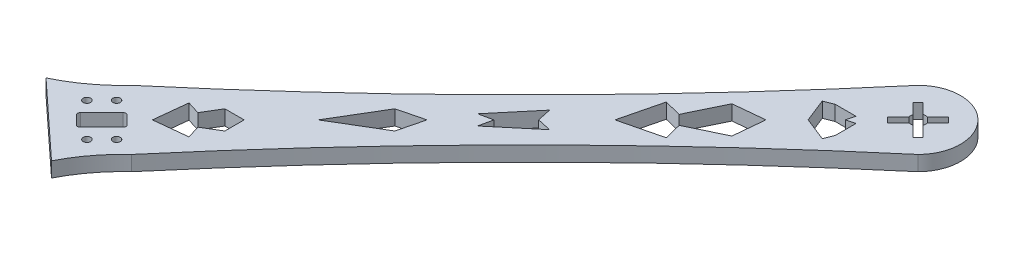
SolidWorks part; units mm, degrees
ref_plane "Front Plane" through (0, 0, 0) normal (0, 0, 1) x (1, 0, 0)
ref_plane "Top Plane" through (0, 0, 0) normal (0, 1, 0) x (1, 0, 0)
ref_plane "Right Plane" through (0, 0, 0) normal (1, 0, 0) x (0, 0, -1)
sketch "Sketch1" plane through (0, 0, 0) normal (0, 1, 0) x (1, 0, 0)
  line L4 (187.3513, 164.2611) -> (185.6543, 165.9582)
  line L5 (185.6543, 165.9582) -> (182.1188, 162.4226)
  line L6 (187.3513, 164.2611) -> (183.8158, 160.7256)
  line L7 (47.8787, 29.3076) -> (50.7071, 26.4792)
  line L8 (50.7071, 25.065) -> (43.636, 17.9939)
  line L9 (42.2218, 17.9939) -> (39.3934, 20.8224)
  line L10 (46.4645, 29.3076) -> (39.3934, 22.2366)
  line L11 (23.6, 26.4792) -> (48.4893, 3.4306)
  line L13 (187.3513, 155.7855) -> (183.8158, 159.321)
  line L14 (185.6543, 154.0884) -> (182.1188, 157.624)
  line L15 (185.6543, 154.0884) -> (187.3513, 155.7855)
  line L16 (177.1787, 154.0884) -> (180.7142, 157.624)
  line L17 (175.4816, 155.7855) -> (179.0171, 159.321)
  line L18 (175.4816, 155.7855) -> (177.1787, 154.0884)
  line L19 (175.4816, 164.2611) -> (179.0171, 160.7256)
  line L20 (177.1787, 165.9582) -> (180.7142, 162.4226)
  line L21 (177.1787, 165.9582) -> (175.4816, 164.2611)
  line L22 (186.5028, 165.1096) -> (191.4182, 170.025)
  arc A4 (43.636, 17.9939) -> (42.2218, 17.9939) centre (42.9289, 18.701) cw
  arc A5 (50.7071, 26.4792) -> (50.7071, 25.065) centre (50, 25.7721) cw
  arc A6 (39.3934, 22.2366) -> (39.3934, 20.8224) centre (40.1005, 21.5295) ccw
  arc A7 (47.8787, 29.3076) -> (46.4645, 29.3076) centre (47.1716, 28.6005) ccw
  circle A8 centre (41.8683, 31.7825) radius 1.25
  circle A9 centre (36.9185, 26.8328) radius 1.25
  circle A10 centre (48.2322, 15.5191) radius 1.25
  circle A11 centre (53.182, 20.4688) radius 1.25
  arc A12 (23.6, 26.4792) -> (40, 38.6005) centre (0, 75.5648) ccw
  arc A13 (48.4893, 3.4306) -> (59.9937, 18.6068) centre (96.9761, -21.3765) cw
  arc A14 (171.4214, 170.0219) -> (191.4151, 150.0282) centre (181.4165, 160.0233) cw
  arc A15 (40, 38.6005) -> (171.4214, 170.0219) centre (-675.445, 885.4669) ccw
  arc A16 (59.9937, 18.6068) -> (191.4151, 150.0282) centre (906.86, -696.8381) cw
  arc A17 (179.0171, 160.7256) -> (179.0171, 159.321) centre (181.4165, 160.0233) ccw
  arc A18 (182.1188, 162.4226) -> (180.7142, 162.4226) centre (181.4165, 160.0233) ccw
  arc A19 (180.7142, 157.624) -> (182.1188, 157.624) centre (181.4165, 160.0233) ccw
  arc A20 (183.8158, 159.321) -> (183.8158, 160.7256) centre (181.4165, 160.0233) ccw
  point P16 (186.5028, 165.1096)
  point P30 (42.9289, 17.2868)
  point P33 (51.4142, 25.7721)
  point P37 (40.8076, 19.4081)
  point P40 (49.2929, 27.8934)
  point P58 (181.4165, 160.0233)
  dimension "D5" = 1
  dimension "D6" = 2.5
  dimension "D7" = 2.5
  dimension "D12" = 5
  dimension "D2" = 3
  dimension "D3" = 12
  dimension "D8" = 5
  dimension "D9" = 2.5
  dimension "D10" = 5
  dimension "D11" = 2.5
  dimension "D13" = 5
  dimension "D14" = 1.2
  dimension "D15" = 4
extrude "Boss-Extrude9" add sketch "Sketch1" along normal blind 5
sketch "Sketch2" plane through (0, 0, 0) normal (0, 1, 0) x (1, 0, 0)
  line L3 (70.4673, 49.0689) -> (71.6058, 49.1569)
  line L4 (157.9097, 145.5071) -> (157.489, 138.0785)
  line L5 (71.6058, 49.1569) -> (68.8007, 37.8473)
  line L6 (150.2385, 135.1234) -> (146.6496, 133.6606)
  line L7 (141.2693, 119.8744) -> (135.2151, 120.2172)
  line L8 (132.4109, 113.5693) -> (130.5478, 109.1524)
  line L9 (126.2401, 104.8444) -> (120.4038, 105.1749)
  line L11 (111.6474, 90.251) -> (105.3921, 90.6052)
  line L12 (102.8647, 83.784) -> (101.5014, 80.1045)
  line L13 (89.6683, 75.9453) -> (87.6059, 76.0621)
  line L15 (81.5155, 60.1176) -> (72.4222, 60.6325)
  line L17 (97.1132, 78.7495) -> (96.9312, 75.5341)
  line L18 (132.4109, 113.5693) -> (135.1328, 113.7376)
  line L19 (111.8313, 93.4979) -> (111.6474, 90.251)
  line L20 (68.8007, 37.8473) -> (55.7707, 34.3716)
  line L21 (70.4673, 49.0689) -> (70.5553, 50.2074)
  line L22 (82.0308, 51.0243) -> (71.9523, 50.554)
  line L23 (86.7802, 65.3826) -> (87.6059, 76.0621)
  line L24 (102.8647, 83.784) -> (105.5724, 84.1757)
  line L25 (81.5155, 60.1176) -> (82.0308, 51.0243)
  line L26 (97.3428, 68.2712) -> (84.88, 63.4823)
  line L27 (120.1801, 98.7841) -> (119.864, 103.8951)
  line L28 (86.7802, 65.3826) -> (97.4597, 66.2088)
  line L29 (135.1328, 113.7376) -> (134.7939, 119.2187)
  line L30 (145.688, 128.9057) -> (150.6042, 129.2097)
  line L31 (150.6042, 129.2097) -> (150.2385, 135.1234)
  line L32 (157.9097, 145.5071) -> (167.4934, 146.0997)
  line L33 (167.4934, 146.0997) -> (167.213, 150.0999)
  line L34 (167.213, 150.0999) -> (162.372, 149.383)
  line L35 (162.372, 149.383) -> (160.8369, 139.443)
  line L36 (160.8369, 139.443) -> (157.489, 138.0785)
  line L37 (146.6496, 133.6606) -> (145.688, 128.9057)
  line L38 (97.3428, 68.2712) -> (97.4597, 66.2088)
  line L39 (135.2151, 120.2172) -> (134.7939, 119.2187)
  line L40 (101.5014, 80.1045) -> (100.1466, 75.7163)
  line L41 (120.4038, 105.1749) -> (119.864, 103.8951)
  line L42 (111.8313, 93.4979) -> (105.9206, 92.0316)
  line L43 (105.9206, 92.0316) -> (105.3921, 90.6052)
  line L44 (101.5014, 80.1045) -> (97.1132, 78.7495)
  line L45 (89.6683, 75.9453) -> (84.88, 63.4823)
  line L46 (105.1808, 81.468) -> (105.5724, 84.1757)
  line L47 (72.4222, 60.6325) -> (71.9523, 50.554)
  line L48 (70.5553, 50.2074) -> (59.2459, 47.4017)
  line L49 (59.2459, 47.4017) -> (55.7707, 34.3716)
  line L50 (100.1466, 75.7163) -> (96.9312, 75.5341)
  line L51 (105.1808, 81.468) -> (101.5014, 80.1045)
  line L52 (113.4283, 84.5243) -> (112.0019, 83.9958)
  line L53 (114.8943, 90.435) -> (113.4283, 84.5243)
  line L54 (114.8943, 90.435) -> (111.6474, 90.251)
  line L55 (111.6474, 90.251) -> (112.0019, 83.9958)
  line L56 (126.5709, 99.0082) -> (125.2911, 98.4683)
  line L57 (120.1801, 98.7841) -> (125.2911, 98.4683)
  line L58 (126.2401, 104.8444) -> (126.5709, 99.0082)
  line L59 (134.9646, 111.0157) -> (130.5478, 109.1524)
  line L60 (141.6124, 113.8202) -> (140.6139, 113.399)
  line L61 (135.1328, 113.7376) -> (140.6139, 113.399)
  line L62 (134.9646, 111.0157) -> (135.1328, 113.7376)
  line L63 (141.2693, 119.8744) -> (141.6124, 113.8202)
  line L64 (155.0553, 125.2554) -> (150.3004, 124.2936)
  line L65 (150.6042, 129.2097) -> (156.5178, 128.8444)
  line L66 (150.3004, 124.2936) -> (150.6042, 129.2097)
  line L67 (156.5178, 128.8444) -> (155.0553, 125.2554)
  line L68 (160.8369, 139.443) -> (159.4726, 136.095)
  line L69 (166.9012, 136.516) -> (159.4726, 136.095)
  line L70 (167.4934, 146.0997) -> (171.4935, 145.8196)
  line L71 (170.7769, 140.9786) -> (160.8369, 139.443)
  line L72 (171.4935, 145.8196) -> (170.7769, 140.9786)
  line L73 (166.9012, 136.516) -> (167.4934, 146.0997)
ref_plane "Plane1" through (0, 5, 0) normal (0, 1, 0) x (1, 0, 0)
sketch "Sketch3" plane through (0, 5, 0) normal (0, 1, 0) x (1, 0, 0)
  line L3 (53.5065, 32.1072) -> (54.7107, 43.1433)
  line L4 (54.7107, 43.1433) -> (58.9993, 41.8032)
  line L5 (58.9993, 41.8032) -> (62.3944, 47.4319)
  line L6 (62.3944, 47.4319) -> (68.8304, 47.4319)
  line L7 (81.2114, 59.8135) -> (90.7948, 75.8293)
  line L8 (90.7948, 75.8293) -> (99.3848, 77.9878)
  line L9 (118.033, 96.637) -> (117.0246, 101.3025)
  line L10 (117.0246, 101.3025) -> (106.0534, 88.1876)
  line L11 (106.0534, 88.1876) -> (110.5576, 89.1612)
  line L12 (130.7693, 109.3739) -> (134.1748, 123.1186)
  line L13 (134.1748, 123.1186) -> (139.9029, 121.6994)
  line L14 (139.9029, 121.6994) -> (145.6504, 133.5853)
  line L15 (145.6504, 133.5853) -> (155.9897, 134.5955)
  line L16 (163.0415, 141.6477) -> (159.9467, 149.4582)
  line L17 (159.9467, 149.4582) -> (163.0415, 150.6844)
  line L18 (163.0415, 150.6844) -> (169.9988, 150.6844)
  line L19 (169.9988, 150.6844) -> (169.2463, 147.8528)
  line L20 (68.8308, 40.9959) -> (68.8304, 47.4319)
  line L21 (63.2022, 37.6005) -> (68.8308, 40.9959)
  line L22 (64.5425, 33.312) -> (63.2022, 37.6005)
  line L23 (53.5065, 32.1072) -> (64.5425, 33.312)
  line L24 (97.2267, 69.3977) -> (99.3848, 77.9878)
  line L25 (81.2114, 59.8135) -> (97.2267, 69.3977)
  line L26 (122.6986, 95.6287) -> (109.5843, 84.657)
  line L27 (109.5843, 84.657) -> (110.5576, 89.1612)
  line L28 (118.033, 96.637) -> (122.6986, 95.6287)
  line L29 (130.7693, 109.3739) -> (144.5139, 112.7801)
  line L30 (144.5139, 112.7801) -> (143.0944, 118.5081)
  line L31 (143.0944, 118.5081) -> (154.98, 124.2561)
  line L32 (154.98, 124.2561) -> (155.9897, 134.5955)
  line L33 (163.0415, 141.6477) -> (170.8521, 138.5533)
  line L34 (172.0779, 148.6054) -> (169.2463, 147.8528)
  line L35 (172.0782, 141.6481) -> (172.0779, 148.6054)
  line L36 (170.8521, 138.5533) -> (172.0782, 141.6481)
extrude "Cut-Extrude1" cut sketch "Sketch3" against normal blind 10
